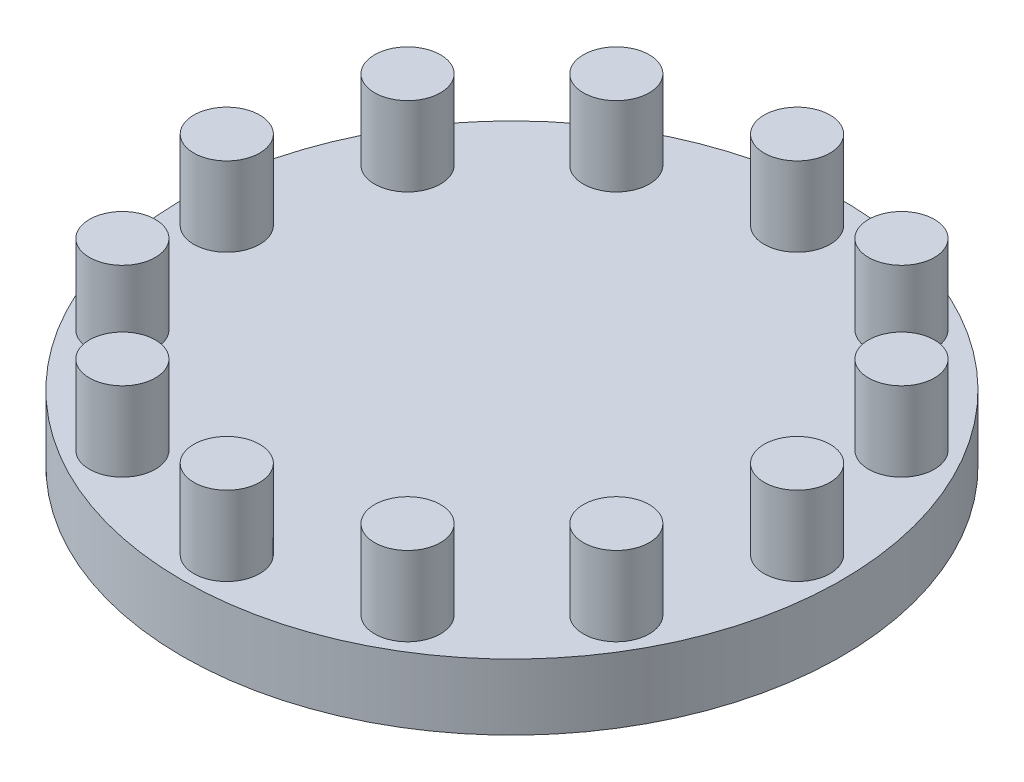
SolidWorks part; units mm, degrees
ref_plane "Alzado" through (0, 0, 0) normal (0, 0, 1) x (1, 0, 0)
ref_plane "Planta" through (0, 0, 0) normal (0, 1, 0) x (1, 0, 0)
ref_plane "Vista lateral" through (0, 0, 0) normal (1, 0, 0) x (0, 0, -1)
sketch "Croquis3" plane through (0, 0, 0) normal (0, 1, 0) x (1, 0, 0)
  circle A0 centre (0, 0) radius 50
  dimension "D1" = 100
extrude "Saliente-Extruir2" add sketch "Croquis3" along normal blind 10
sketch "Croquis4" plane through (0, 10, 0) normal (0, 1, 0) x (1, 0, 0)
  circle A0 centre (0, 43.2642) radius 5
  dimension "D1" = 10
extrude "Saliente-Extruir3" add sketch "Croquis4" along normal blind 12
pattern_circular "MatrizC1" count 12 over 360 about axis through (0, 0, 0) along (0, 1, 0) of "Saliente-Extruir3"
